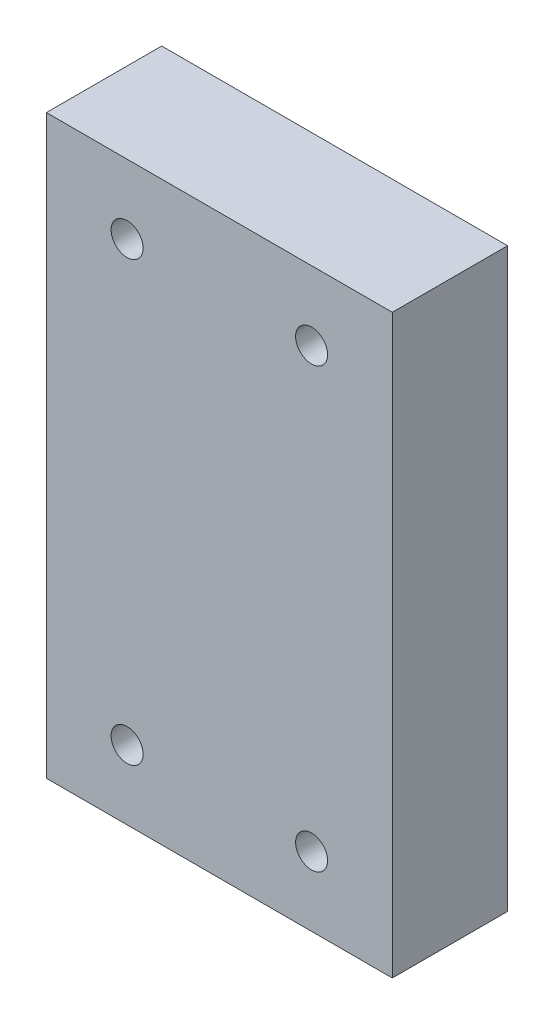
SolidWorks part; units mm, degrees
ref_plane "Front Plane" through (0, 0, 0) normal (0, 0, 1) x (1, 0, 0)
ref_plane "Top Plane" through (0, 0, 0) normal (0, 1, 0) x (1, 0, 0)
ref_plane "Right Plane" through (0, 0, 0) normal (1, 0, 0) x (0, 0, -1)
sketch "Sketch1" plane through (0, 0, 0) normal (0, 0, 1) x (1, 0, 0)
  line L0 (0, 25) -> (0, 0) construction
  line L1 (15, -25) -> (-15, -25)
  line L2 (15, -25) -> (15, 25)
  line L3 (15, 25) -> (-15, 25)
  line L4 (-15, -25) -> (-15, 25)
  line L5 (15, -25) -> (-15, 25) construction
  line L6 (15, 25) -> (-15, -25) construction
  circle A0 centre (-8, 19) radius 1.3874
  circle A1 centre (8, 19) radius 1.3874
  circle A2 centre (8, -19) radius 1.3874
  circle A3 centre (-8, -19) radius 1.3874
  point P0 (0, 0)
  point P9 (0, 0)
  point P17 (0, 0)
  dimension "D3" = 16
  dimension "D4" = 16
  dimension "D5" = 38
  dimension "D6" = 38
  dimension "D1" = 30
  dimension "D2" = 50
  dimension "D7" = 19
extrude "Boss-Extrude1" add sketch "Sketch1" along normal blind 10
sketch "Sketch3" plane through (-15, 0, 0) normal (-1, 0, 0) x (0, 0, 1)
  line L0 (5, 25) -> (5, 0) construction
  line L1 (10, 25) -> (0, 25) construction
  line L2 (5, 0) -> (0, 0) construction
  circle A0 centre (5, 12.5) radius 2
  circle A1 centre (5, -12.5) radius 2
  dimension "D1" = 25
  dimension "D2" = 4
extrude "Cut-Extrude1" cut sketch "Sketch3" against normal blind 10
